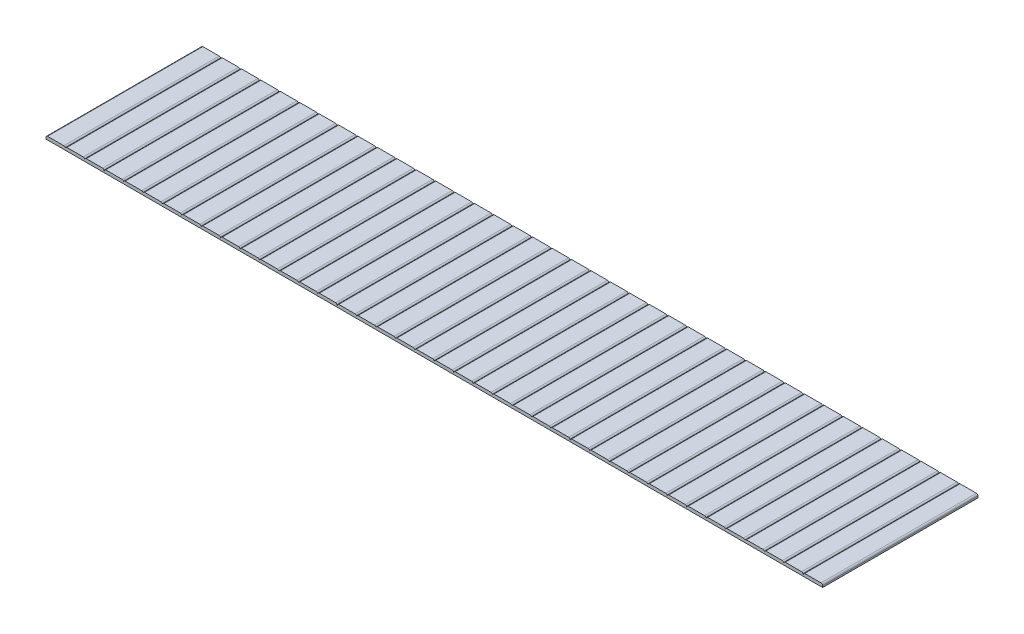
SolidWorks part; units mm, degrees
ref_plane "Front Plane" through (0, 0, 0) normal (0, 0, 1) x (1, 0, 0)
ref_plane "Top Plane" through (0, 0, 0) normal (0, 1, 0) x (1, 0, 0)
ref_plane "Right Plane" through (0, 0, 0) normal (1, 0, 0) x (0, 0, -1)
sketch "bottom floor" plane through (0, 0, 0) normal (0, 1, 0) x (1, 0, 0)
  line L0 (0, 0) -> (-4876.8, 0) construction
  line L1 (-4876.8, -6096) -> (-4876.8, -4927.6) construction
  line L2 (-6096, -6096) -> (-3657.6, -6096)
  line L3 (-6096, -6096) -> (-6096, 6096)
  line L4 (-6096, 6096) -> (-3657.6, 6096)
  line L5 (-3657.6, -6096) -> (-3657.6, 6096)
  line L6 (-6096, -6096) -> (-3657.6, 6096) construction
  line L7 (-6096, 6096) -> (-3657.6, -6096) construction
  line L8 (-5791.2, -5943.6) -> (-3962.4, -5943.6)
  line L9 (-5791.2, -5943.6) -> (-5791.2, -3911.6)
  line L10 (-5791.2, -3911.6) -> (-3962.4, -3911.6)
  line L11 (-3962.4, -5943.6) -> (-3962.4, -3911.6)
  line L12 (-5791.2, -5943.6) -> (-3962.4, -3911.6) construction
  line L13 (-5791.2, -3911.6) -> (-3962.4, -5943.6) construction
  line L14 (-3657.6, -2743.2) -> (-3695.7, -2743.2) construction
  line L15 (-4064, -381) -> (-4064, -406.4) construction
  line L16 (-3733.8, -3657.6) -> (-3657.6, -3657.6)
  line L17 (-3733.8, -3657.6) -> (-3733.8, -1828.8)
  line L18 (-3733.8, -1828.8) -> (-3657.6, -1828.8)
  line L19 (-3657.6, -3657.6) -> (-3657.6, -1828.8)
  line L20 (-3733.8, -3657.6) -> (-3657.6, -1828.8) construction
  line L21 (-3733.8, -1828.8) -> (-3657.6, -3657.6) construction
  line L22 (0, 0) -> (4876.8, 0) construction
  line L23 (-4445, -685.8) -> (-3683, -685.8)
  line L24 (-4445, -685.8) -> (-4445, -76.2)
  line L25 (-4445, -76.2) -> (-3683, -76.2)
  line L26 (-3683, -685.8) -> (-3683, -76.2)
  line L27 (-4445, -685.8) -> (-3683, -76.2) construction
  line L28 (-4445, -76.2) -> (-3683, -685.8) construction
  line L29 (-3657.6, 0) -> (-6096, 0)
  line L30 (-4800.6, -228.6) -> (-4800.6, -635) construction
  line L31 (-5181.6, -1524) -> (-6096, -1524)
  line L32 (-5181.6, -1524) -> (-5181.6, 1524)
  line L33 (-5181.6, 0) -> (-6096, 0)
  line L34 (-6096, -1524) -> (-6096, 1524)
  line L35 (3657.6, 6096) -> (6096, 6096)
  line L36 (3657.6, 6096) -> (3657.6, -6096)
  line L37 (3657.6, -6096) -> (6096, -6096)
  line L38 (6096, 6096) -> (6096, -6096)
  line L39 (3657.6, 6096) -> (6096, -6096) construction
  line L40 (3657.6, -6096) -> (6096, 6096) construction
  line L41 (-4064, -76.2) -> (-4064, -177.8) construction
  line L42 (-4368.8, -635) -> (-3759.2, -635)
  line L43 (-4368.8, -635) -> (-4368.8, -177.8)
  line L44 (-4368.8, -177.8) -> (-3759.2, -177.8)
  line L45 (-3759.2, -635) -> (-3759.2, -177.8)
  line L46 (-4368.8, -635) -> (-3759.2, -177.8) construction
  line L47 (-4368.8, -177.8) -> (-3759.2, -635) construction
  line L48 (6096, 3962.4) -> (6057.9, 3962.4) construction
  line L49 (5791.2, 5105.4) -> (6096, 5105.4) construction
  line L50 (6019.8, 3200.4) -> (6096, 3200.4)
  line L51 (6019.8, 3200.4) -> (6019.8, 4724.4)
  line L52 (6019.8, 4724.4) -> (6096, 4724.4)
  line L53 (6096, 3200.4) -> (6096, 4724.4)
  line L54 (6019.8, 3200.4) -> (6096, 4724.4) construction
  line L55 (6019.8, 4724.4) -> (6096, 3200.4) construction
  line L56 (5486.4, 4800.6) -> (6096, 4800.6)
  line L57 (5486.4, 4800.6) -> (5486.4, 5410.2)
  line L58 (5486.4, 5410.2) -> (6096, 5410.2)
  line L59 (6096, 4800.6) -> (6096, 5410.2)
  line L60 (5486.4, 4800.6) -> (6096, 5410.2) construction
  line L61 (5486.4, 5410.2) -> (6096, 4800.6) construction
  line L62 (5638.8, 4953) -> (5943.6, 4953)
  line L63 (5638.8, 4953) -> (5638.8, 5257.8)
  line L64 (5638.8, 5257.8) -> (5943.6, 5257.8)
  line L65 (5943.6, 4953) -> (5943.6, 5257.8)
  line L66 (5638.8, 4953) -> (5943.6, 5257.8) construction
  line L67 (5638.8, 5257.8) -> (5943.6, 4953) construction
  line L68 (5638.8, 2667) -> (5943.6, 2971.8) construction
  line L69 (5638.8, 2971.8) -> (5943.6, 2667) construction
  line L70 (5486.4, 2514.6) -> (6096, 3124.2) construction
  line L71 (5486.4, 3124.2) -> (6096, 2514.6) construction
  line L72 (5791.2, 2819.4) -> (6096, 2819.4) construction
  line L73 (5943.6, 2971.8) -> (5943.6, 2667)
  line L74 (5638.8, 2667) -> (5943.6, 2667)
  line L75 (5638.8, 2971.8) -> (5638.8, 2667)
  line L76 (5638.8, 2971.8) -> (5943.6, 2971.8)
  line L77 (6096, 3124.2) -> (6096, 2514.6)
  line L78 (5486.4, 2514.6) -> (6096, 2514.6)
  line L79 (5486.4, 3124.2) -> (5486.4, 2514.6)
  line L80 (5486.4, 3124.2) -> (6096, 3124.2)
  line L81 (6019.8, 3200.4) -> (6096, 3200.4)
  line L82 (4876.8, 0) -> (3657.6, 0) construction
  line L83 (3657.6, 2133.6) -> (3657.6, 5791.2)
  line L84 (3657.6, 2133.6) -> (3733.8, 2133.6)
  line L85 (3657.6, 5791.2) -> (3733.8, 5791.2)
  line L86 (3733.8, 2133.6) -> (3733.8, 5791.2)
  line L87 (3733.8, -2133.6) -> (3733.8, -5791.2)
  line L88 (3657.6, -5791.2) -> (3733.8, -5791.2)
  line L89 (3657.6, -2133.6) -> (3733.8, -2133.6)
  line L90 (3657.6, -2133.6) -> (3657.6, -5791.2)
  line L91 (3733.8, 3962.4) -> (6057.9, 3962.4) construction
  line L92 (-5181.6, -1524) -> (-6096, 0) construction
  line L93 (3733.8, -1828.8) -> (3657.6, -1828.8)
  line L94 (3733.8, -1828.8) -> (3733.8, 1828.8)
  line L95 (3733.8, 1828.8) -> (3657.6, 1828.8)
  line L96 (3657.6, -1828.8) -> (3657.6, 1828.8)
  line L97 (3733.8, -1828.8) -> (3657.6, 1828.8) construction
  line L98 (3733.8, 1828.8) -> (3657.6, -1828.8) construction
  line L99 (-5181.6, 0) -> (-6096, -1524) construction
  line L100 (-5105.4, -381) -> (-4495.8, -381)
  line L101 (-5105.4, -381) -> (-5105.4, -76.2)
  line L102 (-5105.4, -76.2) -> (-4495.8, -76.2)
  line L103 (-4495.8, -381) -> (-4495.8, -76.2)
  line L104 (-5105.4, -381) -> (-4495.8, -76.2) construction
  line L105 (-5105.4, -76.2) -> (-4495.8, -381) construction
  line L106 (-6096, -1524) -> (-3657.6, -1524)
  line L107 (-3657.6, -1524) -> (-4304.1784, -2170.5784)
  line L108 (-6096, -1600.2) -> (-6096, -3124.2)
  line L109 (-6096, -1600.2) -> (-5486.4, -1600.2)
  line L110 (-6096, -3124.2) -> (-5486.4, -3124.2)
  line L111 (-5486.4, -1600.2) -> (-5486.4, -3124.2)
  line L112 (-3352.8, 0) -> (-3352.8, -1524)
  line L113 (-3657.6, 0) -> (-609.6, 0)
  line L114 (-3657.6, 0) -> (-3657.6, -1524)
  line L115 (-3657.6, -1524) -> (-609.6, -1524)
  line L116 (-609.6, 0) -> (-609.6, -1524)
  line L117 (-3048, 0) -> (-3048, -1524)
  line L118 (-2743.2, 0) -> (-2743.2, -1524)
  line L119 (-2438.4, 0) -> (-2438.4, -1524)
  line L120 (-2133.6, 0) -> (-2133.6, -1524)
  line L121 (-1828.8, 0) -> (-1828.8, -1524)
  line L122 (-1524, 0) -> (-1524, -1524)
  line L123 (-1219.2, 0) -> (-1219.2, -1524)
  line L124 (-914.4, 0) -> (-914.4, -1524)
  line L125 (5181.6, -6096) -> (5181.6, -2133.6)
  line L126 (3886.2, -6019.8) -> (5105.4, -6019.8)
  line L127 (3886.2, -6019.8) -> (3886.2, -5105.4)
  line L128 (3886.2, -5105.4) -> (5105.4, -5105.4)
  line L129 (5105.4, -6019.8) -> (5105.4, -5105.4)
  line L130 (3886.2, -6019.8) -> (5105.4, -5105.4) construction
  line L131 (3886.2, -5105.4) -> (5105.4, -6019.8) construction
  line L132 (5181.6, -2133.6) -> (6096, -2133.6)
  line L133 (5334, -533.4) -> (5334, -76.2)
  line L134 (4267.2, -1295.4) -> (5486.4, -1295.4)
  line L135 (4267.2, -1295.4) -> (4267.2, 1295.4)
  line L136 (4267.2, 1295.4) -> (5486.4, 1295.4)
  line L137 (5486.4, -1295.4) -> (5486.4, 1295.4)
  line L138 (4267.2, -1295.4) -> (5486.4, 1295.4) construction
  line L139 (4267.2, 1295.4) -> (5486.4, -1295.4) construction
  line L140 (5334, -1143) -> (5943.6, -1143)
  line L141 (5334, -1143) -> (5334, -685.8)
  line L142 (5334, -685.8) -> (5943.6, -685.8)
  line L143 (5943.6, -1143) -> (5943.6, -685.8)
  line L144 (5334, -1143) -> (5943.6, -685.8) construction
  line L145 (5334, -685.8) -> (5943.6, -1143) construction
  line L146 (5334, -76.2) -> (5943.6, -76.2)
  line L147 (5943.6, -533.4) -> (5943.6, -76.2)
  line L148 (5334, -533.4) -> (5943.6, -533.4)
  line L149 (5334, 76.2) -> (5334, 533.4)
  line L150 (5334, 533.4) -> (5943.6, 533.4)
  line L151 (5943.6, 76.2) -> (5943.6, 533.4)
  line L152 (5334, 76.2) -> (5943.6, 76.2)
  line L153 (5334, 685.8) -> (5334, 1143)
  line L154 (5334, 1143) -> (5943.6, 1143)
  line L155 (5943.6, 685.8) -> (5943.6, 1143)
  line L156 (5334, 685.8) -> (5943.6, 685.8)
  line L157 (4876.8, 0) -> (4876.8, -1295.4) construction
  line L158 (4419.6, -685.8) -> (3810, -1143) construction
  line L159 (4419.6, -1143) -> (3810, -685.8) construction
  line L160 (4419.6, 685.8) -> (3810, 685.8)
  line L161 (3810, 685.8) -> (3810, 1143)
  line L162 (4419.6, 1143) -> (3810, 1143)
  line L163 (4419.6, 685.8) -> (4419.6, 1143)
  line L164 (4419.6, 76.2) -> (3810, 76.2)
  line L165 (3810, 76.2) -> (3810, 533.4)
  line L166 (4419.6, 533.4) -> (3810, 533.4)
  line L167 (4419.6, 76.2) -> (4419.6, 533.4)
  line L168 (4419.6, -533.4) -> (3810, -533.4)
  line L169 (3810, -533.4) -> (3810, -76.2)
  line L170 (4419.6, -76.2) -> (3810, -76.2)
  line L171 (3810, -1143) -> (3810, -685.8)
  line L172 (4419.6, -685.8) -> (3810, -685.8)
  line L173 (4419.6, -1143) -> (4419.6, -685.8)
  line L174 (4419.6, -1143) -> (3810, -1143)
  line L175 (4419.6, -533.4) -> (4419.6, -76.2)
  line L176 (-5105.4, 76.2) -> (-4495.8, 381) construction
  line L177 (-5105.4, 381) -> (-4495.8, 76.2) construction
  line L178 (-5181.6, 0) -> (-6096, 1524) construction
  line L179 (-5181.6, 1524) -> (-6096, 0) construction
  line L180 (-4368.8, 177.8) -> (-3759.2, 635) construction
  line L181 (-4368.8, 635) -> (-3759.2, 177.8) construction
  line L182 (-4064, 76.2) -> (-4064, 177.8) construction
  line L183 (-4800.6, 228.6) -> (-4800.6, 635) construction
  line L184 (-4445, 76.2) -> (-3683, 685.8) construction
  line L185 (-4445, 685.8) -> (-3683, 76.2) construction
  line L186 (-3733.8, 1828.8) -> (-3657.6, 3657.6) construction
  line L187 (-3733.8, 3657.6) -> (-3657.6, 1828.8) construction
  line L188 (-4064, 381) -> (-4064, 406.4) construction
  line L189 (-3657.6, 2743.2) -> (-3695.7, 2743.2) construction
  line L190 (-5791.2, 3911.6) -> (-3962.4, 5943.6) construction
  line L191 (-5791.2, 5943.6) -> (-3962.4, 3911.6) construction
  line L192 (-4876.8, 6096) -> (-4876.8, 4927.6) construction
  line L193 (-5486.4, 1600.2) -> (-5486.4, 3124.2)
  line L194 (-6096, 3124.2) -> (-5486.4, 3124.2)
  line L195 (-6096, 1600.2) -> (-5486.4, 1600.2)
  line L196 (-6096, 1600.2) -> (-6096, 3124.2)
  line L197 (-3657.6, 1524) -> (-4304.1784, 2170.5784)
  line L198 (-6096, 1524) -> (-3657.6, 1524)
  line L199 (-4495.8, 381) -> (-4495.8, 76.2)
  line L200 (-5105.4, 76.2) -> (-4495.8, 76.2)
  line L201 (-5105.4, 381) -> (-5105.4, 76.2)
  line L202 (-5105.4, 381) -> (-4495.8, 381)
  line L203 (-3759.2, 635) -> (-3759.2, 177.8)
  line L204 (-4368.8, 177.8) -> (-3759.2, 177.8)
  line L205 (-4368.8, 635) -> (-4368.8, 177.8)
  line L206 (-4368.8, 635) -> (-3759.2, 635)
  line L207 (-5181.6, 1524) -> (-6096, 1524)
  line L208 (-3683, 685.8) -> (-3683, 76.2)
  line L209 (-4445, 76.2) -> (-3683, 76.2)
  line L210 (-4445, 685.8) -> (-4445, 76.2)
  line L211 (-4445, 685.8) -> (-3683, 685.8)
  line L212 (-3657.6, 3657.6) -> (-3657.6, 1828.8)
  line L213 (-3733.8, 1828.8) -> (-3657.6, 1828.8)
  line L214 (-3733.8, 3657.6) -> (-3733.8, 1828.8)
  line L215 (-3733.8, 3657.6) -> (-3657.6, 3657.6)
  line L216 (-3962.4, 5943.6) -> (-3962.4, 3911.6)
  line L217 (-5791.2, 3911.6) -> (-3962.4, 3911.6)
  line L218 (-5791.2, 5943.6) -> (-5791.2, 3911.6)
  line L219 (-5791.2, 5943.6) -> (-3962.4, 5943.6)
  line L220 (-6096, 6096) -> (-3657.6, 6096)
  circle A0 centre (-4800.6, -635) radius 254
  circle A1 centre (-4064, -127) radius 25.4
  arc A2 (-4304.1784, -2170.5784) -> (-4572, -1524) centre (-3657.6, -1524) cw
  arc A3 (-4304.1784, 2170.5784) -> (-4572, 1524) centre (-3657.6, 1524) ccw
  circle A4 centre (-4064, 127) radius 25.4
  circle A5 centre (-4800.6, 635) radius 254
  point P7 (-4876.8, -4927.6)
  point P20 (-4064, -381)
  point P26 (-3657.6, 6019.8)
  point P27 (4876.8, 0)
  point P30 (-5638.8, -762)
  point P31 (-4800.6, -228.6)
  point P48 (5791.2, 5105.4)
  point P53 (5791.2, 5105.4)
  point P81 (3695.7, 0)
  point P111 (4495.8, -5562.6)
  point P139 (5638.8, -914.4)
  point P173 (4114.8, -914.4)
  point P216 (-5638.8, 762)
  point P217 (-3657.6, -6019.8)
  dimension "D31" = 508
  dimension "D37" = 50.8
  dimension "D1" = 2438.4
  dimension "D2" = 12192
  dimension "D3" = 1828.8
  dimension "D4" = 2032
  dimension "D5" = 152.4
  dimension "D6" = 76.2
  dimension "D7" = 1828.8
  dimension "D8" = 1828.8
  dimension "D9" = 762
  dimension "D10" = 609.6
  dimension "D11" = 50.8
  dimension "D12" = 304.8
  dimension "D13" = 2438.4
  dimension "D14" = 12192
  dimension "D15" = 12192
  dimension "D16" = 76.2
  dimension "D17" = 1524
  dimension "D18" = 76.2
  dimension "D19" = 609.6
  dimension "D20" = 609.6
  dimension "D21" = 304.8
  dimension "D22" = 304.8
  dimension "D23" = 76.2
  dimension "D24" = 914.4
  dimension "D25" = 76.2
  dimension "D26" = 3657.6
  dimension "D27" = 3657.6
  dimension "D28" = 1524
  dimension "D29" = 609.6
  dimension "D30" = 304.8
  dimension "D32" = 76.2
  dimension "D33" = 76.2
  dimension "D34" = 50.8
  dimension "D35" = 609.6
  dimension "D36" = 457.2
  dimension "D38" = 914.4
  dimension "D39" = 45
  dimension "D40" = 609.6
  dimension "D41" = 1524
  dimension "D42" = 76.2
  dimension "D43" = 3048
  dimension "D44" = 1524
  dimension "D45" = 304.8
  dimension "D47" = 1219.2
  dimension "D48" = 914.4
  dimension "D49" = 76.2
  dimension "D50" = 3962.4
  dimension "D51" = 914.4
  dimension "D52" = 76.2
  dimension "D53" = 609.6
  dimension "D54" = 457.2
  dimension "D55" = 152.4
  dimension "D56" = 152.4
  dimension "D58" = 152.4
  dimension "D59" = 304.8
  dimension "D60" = 76.2
  dimension "D61" = 2590.8
  dimension "D62" = 1219.2
  dimension "D63" = 76.2
  dimension "D46" = 9
  dimension "D57" = 4
ref_plane "Plane1" through (0, 2895.6, 0) normal (0, 1, 0) x (1, 0, 0)
sketch "top floor" plane through (0, 2895.6, 0) normal (0, 1, 0) x (1, 0, 0)
  line L0 (0, 0) -> (0, 4876.8) construction
  line L1 (-1524, 3657.6) -> (-1524, 3581.4) construction
  line L2 (-6096, 3657.6) -> (6096, 3657.6)
  line L3 (-6096, 3657.6) -> (-6096, 6096)
  line L4 (-6096, 6096) -> (6096, 6096)
  line L5 (6096, 3657.6) -> (6096, 6096)
  line L6 (-6096, 3657.6) -> (6096, 6096) construction
  line L7 (-6096, 6096) -> (6096, 3657.6) construction
  line L8 (1524, 3657.6) -> (1524, 3581.4) construction
  line L9 (-3048, 3505.2) -> (0, 3505.2)
  line L10 (-3048, 3505.2) -> (-3048, 3657.6)
  line L11 (-3048, 3657.6) -> (0, 3657.6)
  line L12 (0, 3505.2) -> (0, 3657.6)
  line L13 (-3048, 3505.2) -> (0, 3657.6) construction
  line L14 (-3048, 3657.6) -> (0, 3505.2) construction
  line L15 (-5461, 4876.8) -> (-6096, 4876.8) construction
  line L16 (3048, 3505.2) -> (0, 3505.2)
  line L17 (3048, 3505.2) -> (3048, 3657.6)
  line L18 (3048, 3657.6) -> (0, 3657.6)
  line L19 (0, 3505.2) -> (0, 3657.6)
  line L20 (3048, 3505.2) -> (0, 3657.6) construction
  line L21 (3048, 3657.6) -> (0, 3505.2) construction
  line L22 (-5943.6, 5892.8) -> (-4978.4, 5892.8)
  line L23 (-5943.6, 5892.8) -> (-5943.6, 3860.8)
  line L24 (-5943.6, 3860.8) -> (-4978.4, 3860.8)
  line L25 (-4978.4, 5892.8) -> (-4978.4, 3860.8)
  line L26 (-5943.6, 5892.8) -> (-4978.4, 3860.8) construction
  line L27 (-5943.6, 3860.8) -> (-4978.4, 5892.8) construction
  line L28 (-3657.6, 3657.6) -> (-3657.6, 6096)
  line L29 (-3657.6, -6096) -> (-3657.6, 6096) construction
  line L30 (-3657.6, 3657.6) -> (-3011.0216, 4304.1784)
  line L31 (-3657.6, -1524) -> (-6096, -1524)
  line L32 (-4267.2, 4572) -> (-3657.6, 4572)
  line L33 (-4267.2, 4572) -> (-4267.2, 6096)
  line L34 (-4267.2, 6096) -> (-3657.6, 6096)
  line L35 (-3657.6, 4572) -> (-3657.6, 6096)
  line L36 (-4267.2, 4572) -> (-3657.6, 6096) construction
  line L37 (-4267.2, 6096) -> (-3657.6, 4572) construction
  line L38 (-6096, -1524) -> (-6096, 3657.6)
  line L39 (-3657.6, 0) -> (3657.6, 0)
  line L40 (3657.6, 0) -> (6096, 0)
  line L41 (6096, 6096) -> (6096, -6096) construction
  line L42 (6096, 0) -> (6096, 3657.6)
  line L43 (-3657.6, 0) -> (-3657.6, -1524)
  line L44 (3657.6, 6096) -> (3657.6, 3657.6)
  line L45 (3657.6, 6096) -> (3657.6, -6096) construction
  line L46 (5943.6, 3860.8) -> (4978.4, 3860.8)
  line L47 (4978.4, 5892.8) -> (4978.4, 3860.8)
  line L48 (5943.6, 5892.8) -> (4978.4, 5892.8)
  line L49 (5943.6, 5892.8) -> (5943.6, 3860.8)
  line L50 (4267.2, 4572) -> (4267.2, 6096)
  line L51 (4267.2, 4572) -> (3657.6, 4572)
  line L52 (3657.6, 3657.6) -> (3011.0216, 4304.1784)
  line L53 (-1219.2, 5410.2) -> (0, 5410.2)
  line L54 (-2438.4, 5410.2) -> (-1219.2, 5410.2)
  line L55 (-2438.4, 5410.2) -> (-2438.4, 6019.8)
  line L56 (-2438.4, 6019.8) -> (-1219.2, 6019.8)
  line L57 (-1219.2, 5410.2) -> (-1219.2, 6019.8)
  line L58 (-2438.4, 5410.2) -> (-1219.2, 6019.8) construction
  line L59 (-2438.4, 6019.8) -> (-1219.2, 5410.2) construction
  line L60 (-1219.2, 5410.2) -> (-1219.2, 6019.8)
  line L61 (-1219.2, 6019.8) -> (0, 6019.8)
  line L62 (0, 5410.2) -> (0, 6019.8)
  line L63 (-1219.2, 5410.2) -> (0, 6019.8) construction
  line L64 (-1219.2, 6019.8) -> (0, 5410.2) construction
  line L65 (0, 5410.2) -> (1219.2, 5410.2)
  line L66 (0, 5410.2) -> (0, 6019.8)
  line L67 (0, 6019.8) -> (1219.2, 6019.8)
  line L68 (1219.2, 5410.2) -> (1219.2, 6019.8)
  line L69 (0, 5410.2) -> (1219.2, 6019.8) construction
  line L70 (0, 6019.8) -> (1219.2, 5410.2) construction
  line L71 (1219.2, 5410.2) -> (2438.4, 5410.2)
  line L72 (1219.2, 5410.2) -> (1219.2, 6019.8)
  line L73 (1219.2, 6019.8) -> (2438.4, 6019.8)
  line L74 (2438.4, 5410.2) -> (2438.4, 6019.8)
  line L75 (1219.2, 5410.2) -> (2438.4, 6019.8) construction
  line L76 (1219.2, 6019.8) -> (2438.4, 5410.2) construction
  line L77 (-2438.4, 5715) -> (-1828.8, 5715) construction
  line L78 (-1828.8, 5715) -> (-1219.2, 5715) construction
  line L79 (-1143, 5486.4) -> (-685.8, 5486.4)
  line L80 (-2362.2, 5486.4) -> (-1905, 5486.4)
  line L81 (-2362.2, 5486.4) -> (-2362.2, 5943.6)
  line L82 (-2362.2, 5943.6) -> (-1905, 5943.6)
  line L83 (-1905, 5486.4) -> (-1905, 5943.6)
  line L84 (-2362.2, 5486.4) -> (-1905, 5943.6) construction
  line L85 (-2362.2, 5943.6) -> (-1905, 5486.4) construction
  line L86 (-1295.4, 5486.4) -> (-1752.6, 5486.4)
  line L87 (-1295.4, 5486.4) -> (-1295.4, 5943.6)
  line L88 (-1295.4, 5943.6) -> (-1752.6, 5943.6)
  line L89 (-1752.6, 5486.4) -> (-1752.6, 5943.6)
  line L90 (-1295.4, 5486.4) -> (-1752.6, 5943.6) construction
  line L91 (-1295.4, 5943.6) -> (-1752.6, 5486.4) construction
  line L92 (-1143, 5486.4) -> (-1143, 5943.6)
  line L93 (-1143, 5943.6) -> (-685.8, 5943.6)
  line L94 (-685.8, 5486.4) -> (-685.8, 5943.6)
  line L95 (-76.2, 5486.4) -> (-533.4, 5486.4)
  line L96 (-76.2, 5486.4) -> (-76.2, 5943.6)
  line L97 (-76.2, 5943.6) -> (-533.4, 5943.6)
  line L98 (-533.4, 5486.4) -> (-533.4, 5943.6)
  line L99 (-1143, 5486.4) -> (-685.8, 5943.6) construction
  line L100 (-1143, 5943.6) -> (-685.8, 5486.4) construction
  line L101 (-76.2, 5486.4) -> (-533.4, 5943.6) construction
  line L102 (-76.2, 5943.6) -> (-533.4, 5486.4) construction
  line L103 (76.2, 5486.4) -> (533.4, 5486.4)
  line L104 (76.2, 5486.4) -> (76.2, 5943.6)
  line L105 (76.2, 5943.6) -> (533.4, 5943.6)
  line L106 (533.4, 5486.4) -> (533.4, 5943.6)
  line L107 (1143, 5486.4) -> (685.8, 5486.4)
  line L108 (1143, 5486.4) -> (1143, 5943.6)
  line L109 (1143, 5943.6) -> (685.8, 5943.6)
  line L110 (685.8, 5486.4) -> (685.8, 5943.6)
  line L111 (76.2, 5486.4) -> (533.4, 5943.6) construction
  line L112 (76.2, 5943.6) -> (533.4, 5486.4) construction
  line L113 (1143, 5486.4) -> (685.8, 5943.6) construction
  line L114 (1143, 5943.6) -> (685.8, 5486.4) construction
  line L115 (1295.4, 5486.4) -> (1752.6, 5486.4)
  line L116 (1295.4, 5486.4) -> (1295.4, 5943.6)
  line L117 (1295.4, 5943.6) -> (1752.6, 5943.6)
  line L118 (1752.6, 5486.4) -> (1752.6, 5943.6)
  line L119 (2362.2, 5486.4) -> (1905, 5486.4)
  line L120 (2362.2, 5486.4) -> (2362.2, 5943.6)
  line L121 (2362.2, 5943.6) -> (1905, 5943.6)
  line L122 (1905, 5486.4) -> (1905, 5943.6)
  line L123 (1295.4, 5486.4) -> (1752.6, 5943.6) construction
  line L124 (1295.4, 5943.6) -> (1752.6, 5486.4) construction
  line L125 (2362.2, 5486.4) -> (1905, 5943.6) construction
  line L126 (2362.2, 5943.6) -> (1905, 5486.4) construction
  line L127 (-1295.4, 5486.4) -> (-1143, 5486.4) construction
  arc A0 (-3011.0216, 4304.1784) -> (-3657.6, 4572) centre (-3657.6, 3657.6) ccw
  arc A1 (3011.0216, 4304.1784) -> (3657.6, 4572) centre (3657.6, 3657.6) cw
  point P16 (-5461, 4876.8)
  point P33 (-3962.4, 5334)
  point P67 (-2133.6, 5715)
  point P88 (-1524, 5715)
  point P94 (-914.4, 5715)
  point P99 (-304.8, 5715)
  point P104 (304.8, 5715)
  point P109 (914.4, 5715)
  point P114 (1524, 5715)
  point P119 (2133.6, 5715)
  dimension "D1" = 2438.4
  dimension "D2" = 3048
  dimension "D3" = 3048
  dimension "D4" = 152.4
  dimension "D5" = 965.2
  dimension "D6" = 2032
  dimension "D7" = 152.4
  dimension "D8" = 914.4
  dimension "D9" = 45
  dimension "D10" = 609.6
  dimension "D11" = 1524
  dimension "D12" = 1219.2
  dimension "D13" = 609.6
  dimension "D15" = 457.2
  dimension "D17" = 2438.4
  dimension "D18" = 76.2
  dimension "D19" = 76.2
  dimension "D14" = 4
  dimension "D16" = 4
ref_plane "Plane2" through (0, 0, 6019.8) normal (0, 0, 1) x (1, 0, 0)
ref_plane "Plane3" through (0, 0, -6096) normal (0, 0, 1) x (1, 0, 0)
sketch "Sketch1" plane through (0, 0, 0) normal (0, 0, 1) x (1, 0, 0)
  line L0 (6096, 2895.6) -> (5791.2, 2895.6)
  line L1 (6096, 2895.6) -> (6096, 2921)
  line L2 (5791.2, 2895.6) -> (5791.2, 2921)
  line L3 (6070.6, 2946.4) -> (5816.6, 2946.4)
  line L6 (3657.6, 2895.6) -> (6096, 2895.6) construction
  arc A0 (6096, 2921) -> (6070.6, 2946.4) centre (6070.6, 2921) ccw
  arc A1 (5791.2, 2921) -> (5816.6, 2946.4) centre (5816.6, 2921) cw
  point P11 (6096, 2946.4)
  point P14 (5791.2, 2946.4)
  dimension "D3" = 25.4
  dimension "D1" = 50.8
  dimension "D2" = 304.8
  dimension "D4" = 0
extrude "Boss-Extrude1" add sketch "Sketch1" against normal blind 2438.4
pattern_linear "LPattern1" count 1 spacing 2.54 along (1, 0, 0) count 40 spacing 304.8 along (-1, 0, 0) of "Boss-Extrude1"
